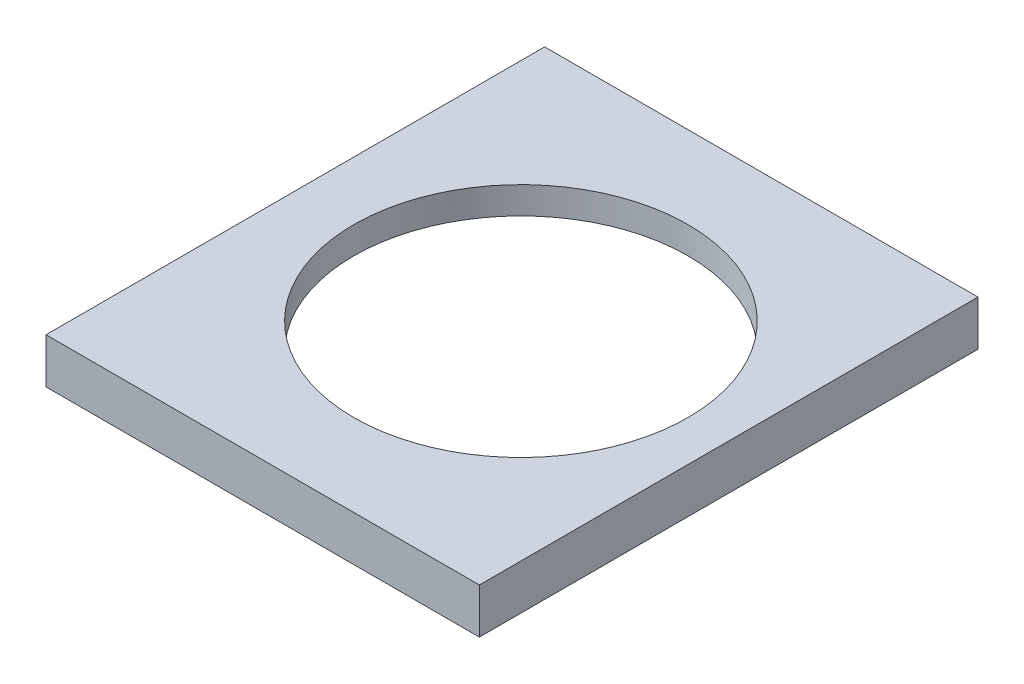
SolidWorks part; units mm, degrees
ref_plane "Front Plane" through (0, 0, 0) normal (0, 0, 1) x (1, 0, 0)
ref_plane "Top Plane" through (0, 0, 0) normal (0, 1, 0) x (1, 0, 0)
ref_plane "Right Plane" through (0, 0, 0) normal (1, 0, 0) x (0, 0, -1)
sketch "Sketch1" plane through (0, 0, 0) normal (0, 1, 0) x (1, 0, 0)
  line L1 (-24.975, -27.6) -> (23, -27.6)
  line L2 (-24.975, -27.6) -> (-24.975, 27.6)
  line L3 (-24.975, 27.6) -> (23, 27.6)
  line L4 (23, -27.6) -> (23, 27.6)
  point P0 (0, 0)
  point P6 (0, 0)
extrude "Boss-Extrude1" add sketch "Sketch1" along normal blind 3
sketch "Sketch2" plane through (0, 3, 0) normal (0, 1, 0) x (1, 0, 0)
  line L0 (-19.3179, 18.49) -> (18.1221, 18.49)
  line L1 (-19.3179, 18.49) -> (-19.3179, -18.95)
  line L2 (-19.3179, -18.95) -> (18.1221, -18.95)
  line L3 (18.1221, 18.49) -> (18.1221, -18.95)
  circle A0 centre (-19.3179, 18.49) radius 1.25
  circle A1 centre (18.1221, 18.49) radius 1.25
  circle A2 centre (-19.3179, -18.95) radius 1.25
  circle A3 centre (18.1221, -18.95) radius 1.25
sketch "Sketch3" plane through (0, 3, 0) normal (0, 1, 0) x (1, 0, 0)
  circle A0 centre (0, 0) radius 18.5
sketch "Sketch4" plane through (0, 3, 0) normal (0, 1, 0) x (1, 0, 0)
  line L1 (-16.7358, 33.9203) -> (16.2875, 33.9203)
  line L2 (-16.7358, 33.9203) -> (-16.7358, 13.0921)
  line L3 (-16.7358, 13.0921) -> (16.2875, 13.0921)
  line L4 (16.2875, 33.9203) -> (16.2875, 13.0921)
  line L5 (-16.7358, 33.9203) -> (16.2875, 13.0921) construction
  line L6 (-16.7358, 13.0921) -> (16.2875, 33.9203) construction
  point P0 (-0.2241, 23.5062)
extrude "Cut-Extrude1" [suppressed] cut sketch "Sketch4" against normal blind 8 contours L2 L1 L4 L3
sketch "Sketch5" plane through (0, 3, 0) normal (0, 1, 0) x (1, 0, 0)
  circle A0 centre (-19.3179, 18.49) radius 2
  circle A1 centre (18.1221, 18.49) radius 2
  circle A2 centre (-19.3179, -18.95) radius 2
  circle A3 centre (18.0841, -18.9245) radius 2
extrude "Cut-Extrude2" cut sketch "Sketch3" against normal blind 8
extrude "Cut-Extrude3" [suppressed] cut sketch "Sketch5" against normal blind 2.5
sketch "Sketch7" plane through (0, 0, 0) normal (0, -1, 0) x (1, 0, 0)
  line L0 (-24.975, -27.6) -> (-24.2655, -27.6)
  line L1 (-24.2655, -27.6) -> (-24.2655, 27.6)
  line L2 (-24.2655, 27.6) -> (-24.975, 27.6)
  line L3 (23, 27.6) -> (23, -27.6)
  line L4 (23, -27.6) -> (21.8, -27.6)
  line L5 (23, -27.6) -> (-24.975, -27.6) construction
  line L6 (21.8, -27.6) -> (21.8, 27.6)
  line L7 (21.8, 27.6) -> (23, 27.6)
  line L8 (-24.975, 27.6) -> (-24.975, -27.6)
  line L9 (-24.975, -27.6) -> (-24.975, -26.0038)
  line L11 (21.8, -26.0038) -> (21.8, -27.6)
  point P3 (0, 0)
extrude "Boss-Extrude2" add sketch "Sketch7" along normal blind 2 contours L0 L1 L2 L8 | L6 L7 L3 L4
sketch "Sketch8" plane through (0, 0, 0) normal (0, -1, 0) x (1, 0, 0)
  line L0 (-24.2655, 26.8552) -> (21.8, 26.8552)
  line L1 (-24.2655, -27.6) -> (-24.2655, 27.6) construction
  line L2 (21.8, -27.6) -> (21.8, 27.6) construction
  line L3 (21.8, 26.8552) -> (21.8, 27.6)
  line L4 (21.8, 27.6) -> (-24.2655, 27.6)
  line L5 (-24.2655, 27.6) -> (-24.2655, 26.8552)
  line L6 (-24.2655, -27.6) -> (21.8, -27.6)
  line L7 (21.8, -27.6) -> (21.8, -26.5004)
  line L8 (21.8, -27.6) -> (21.8, 27.6) construction
  line L9 (21.8, -26.5004) -> (-24.2655, -26.5004)
  line L10 (-24.2655, -27.6) -> (-24.2655, 27.6) construction
  line L11 (-24.2655, -26.5004) -> (-24.2655, -27.6)
extrude "Boss-Extrude3" add sketch "Sketch8" along normal blind 2
sketch "Sketch9" plane through (0, 0, 0) normal (0, -1, 0) x (1, 0, 0)
  line L0 (-19.324, 18.9628) -> (18.116, 18.9628)
  line L1 (-19.324, 18.9628) -> (-19.324, -18.4772)
  line L2 (-19.324, -18.4772) -> (18.116, -18.4772)
  line L3 (18.116, 18.9628) -> (18.116, -18.4772)
  circle A0 centre (-19.324, 18.9628) radius 2
  circle A1 centre (18.116, 18.9628) radius 2
  circle A2 centre (-19.324, -18.4772) radius 2
  circle A3 centre (18.116, -18.4772) radius 2
extrude "Cut-Extrude4" cut sketch "Sketch9" against normal blind 2.5 contours A0 | A1 | A2 | A3
